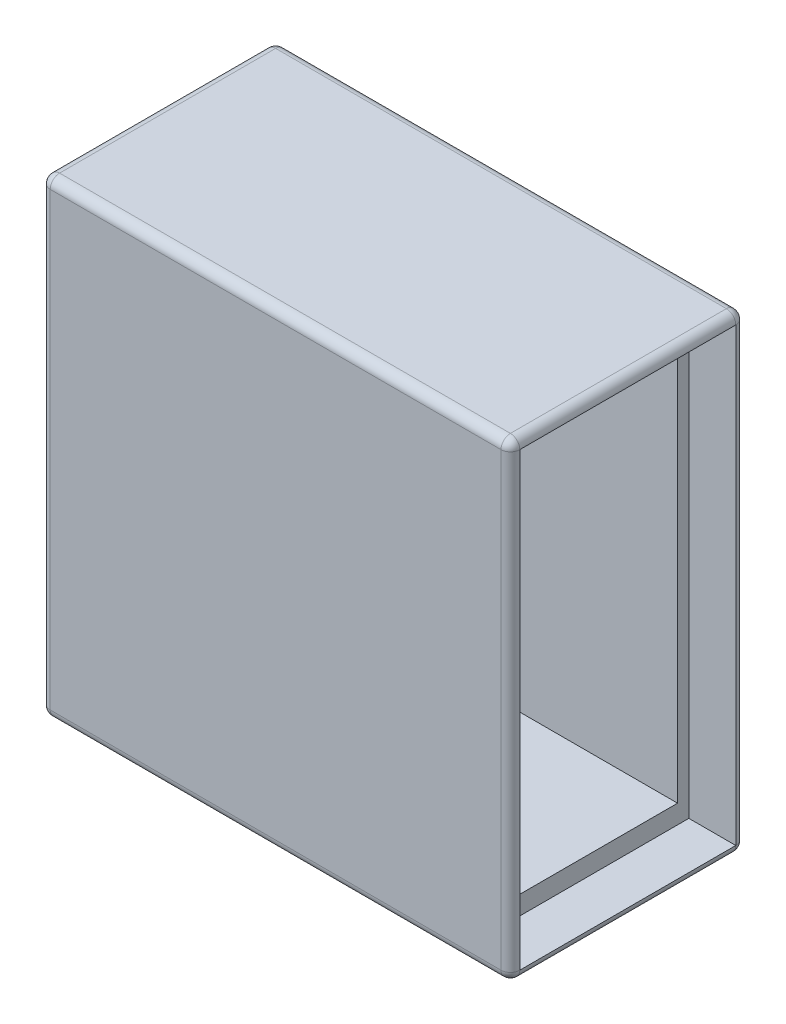
SolidWorks part; units mm, degrees
ref_plane "前视基准面" through (0, 0, 0) normal (0, 0, 1) x (1, 0, 0)
ref_plane "上视基准面" through (0, 0, 0) normal (0, 1, 0) x (1, 0, 0)
ref_plane "右视基准面" through (0, 0, 0) normal (1, 0, 0) x (0, 0, -1)
other "Configuration Table"
sketch "草图1" plane through (0, 0, 0) normal (0, 0, 1) x (1, 0, 0)
  line L0 (0, 0) -> (50, 0)
  line L1 (50, 0) -> (50, 50)
  line L2 (50, 50) -> (0, 50)
  line L3 (0, 50) -> (0, 0)
  dimension "D1" = 50
  dimension "D2" = 50
extrude "凸台-拉伸1" add sketch "草图1" against normal blind 25
shell "抽壳2" thickness 5
sketch "草图2" plane through (0, 0, 0) normal (-1, 0, 0) x (0, 0, 1)
  line L4 (-12.5, 50) -> (-12.5, 0) construction
  line L5 (-25, 50) -> (0, 50) construction
  line L6 (-25, 0) -> (0, 0) construction
  line L7 (-12.5, 28) -> (-29.2401, 28) construction
  line L8 (-12.5, 18.625) -> (-29.2401, 18.625) construction
  line L9 (-12.5, 28) -> (5.4326, 28) construction
  line L10 (-12.5, 18.625) -> (6.1207, 18.625) construction
  line L11 (-12.5, 50) -> (1.7096, 50) construction
  circle A2 centre (-19.5, 18.625) radius 3.125
  circle A3 centre (-19.5, 28) radius 3.125
  circle A4 centre (-5.5, 28) radius 3.125
  circle A5 centre (-5.5, 18.625) radius 3.125
  circle A6 centre (-12.5, 8.125) radius 3.125
  dimension "D1" = 7
  dimension "D2" = 7
  dimension "D5" = 6.25
  dimension "D6" = 6.25
  dimension "D7" = 6.25
  dimension "D8" = 6.25
  dimension "D10" = 6.25
  dimension "D3" = 7
  dimension "D4" = 9.375
  dimension "D9" = 7
  dimension "D11" = 10.5
  dimension "D12" = 22
sketch "草图3" plane through (0, 0, 0) normal (-1, 0, 0) x (0, 0, 1)
  line L0 (-25, 50) -> (0, 50) construction
  line L1 (-25, 50) -> (-25, 0) construction
  line L7 (-12.4883, 45.6021) -> (-12.4883, 35.6479) construction
  circle A0 centre (-12.4883, 40.625) radius 3.75
  point P4 (0, 0)
  point P5 (-12.4883, 35.6479)
  dimension "D3" = 7.5
  dimension "D2" = 12.5117
  dimension "D1" = 9.375
extrude "切除-拉伸3" cut sketch "草图3" against normal blind 17.5
fillet "圆角2" radius 1 12 edges at (25, 0, 0) (0, 0, -12.5) (0, 25, 0) (0, 25, -25) (25, 50, -25) (25, 0, -25) (50, 25, 0) (50, 0, -12.5) (50, 25, -25) (50, 50, -12.5) (25, 50, 0) (0, 50, -12.5)
sketch "草图8" plane through (50, 0, 0) normal (1, 0, 0) x (0, 0, -1)
  line L4 (24, 49) -> (1, 49)
  line L5 (1, 49) -> (1, 1)
  line L6 (1, 1) -> (24, 1)
  line L7 (24, 1) -> (24, 49)
  line L8 (24, 49) -> (1, 49)
  line L9 (1, 49) -> (1, 1)
  line L10 (1, 1) -> (24, 1)
  line L11 (24, 1) -> (24, 49)
  dimension "D1" = 0
extrude "切除-拉伸5" cut sketch "草图8" against normal blind 5
extrude "切除-拉伸6" cut sketch "草图2" against normal blind 10
sketch "草图9" plane through (45, 0, 0) normal (1, 0, 0) x (0, 0, -1)
  line L0 (5, 45) -> (5, 5)
  line L2 (2.2, 3) -> (2.2, 47)
  line L3 (2.2, 47) -> (22.8, 47)
  line L4 (22.8, 47) -> (22.8, 3)
  line L5 (22.8, 3) -> (2.2, 3)
  line L6 (20, 45) -> (5, 45) construction
  line L7 (20, 5) -> (20, 45) construction
  line L8 (5, 45) -> (20, 45)
  line L9 (20, 45) -> (20, 5)
  line L10 (20, 5) -> (5, 5)
  point P4 (0.0791, 24.9768)
  point P8 (2.2, 25)
  dimension "D1" = 2.8
  dimension "D2" = 2
  dimension "D3" = 2.8
  dimension "D4" = 2
extrude "切除-拉伸7" cut sketch "草图9" against normal blind 40
